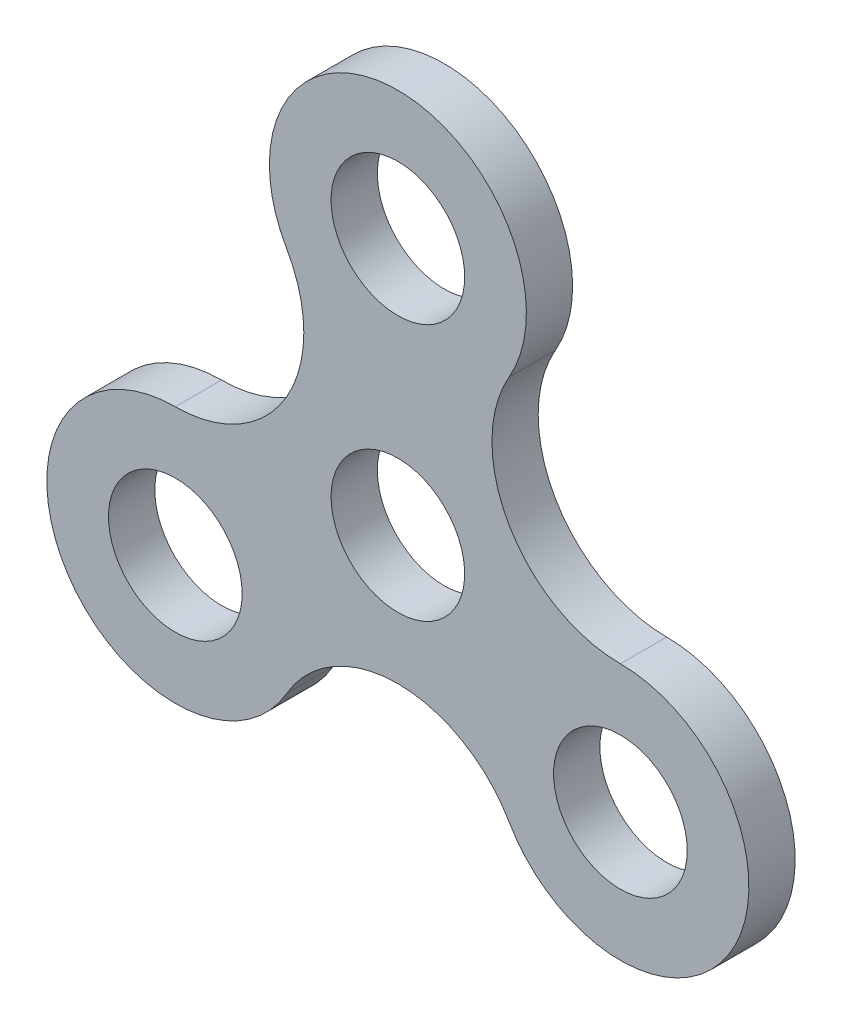
SolidWorks part; units mm, degrees
material "Alloy Steel"
ref_plane "Front Plane" through (0, 0, 0) normal (0, 0, 1) x (1, 0, 0)
ref_plane "Top Plane" through (0, 0, 0) normal (0, 1, 0) x (1, 0, 0)
ref_plane "Right Plane" through (0, 0, 0) normal (1, 0, 0) x (0, 0, -1)
sketch "Sketch1" plane through (0, 0, 0) normal (0, 0, 1) x (1, 0, 0)
  line L0 (0, 0) -> (0, 500) construction
  line L1 (0, 0) -> (-433.0127, -250) construction
  line L2 (0, 0) -> (433.0127, -250) construction
  circle A0 centre (0, 0) radius 750 construction
  circle A1 centre (0, 0) radius 250 construction
  arc A3 (-433.0127, 0) -> (-216.5064, -375) centre (-433.0127, -250) ccw
  arc A4 (216.5064, -375) -> (433.0127, 0) centre (433.0127, -250) ccw
  arc A5 (216.5064, 375) -> (-216.5064, 375) centre (0, 500) ccw
  arc A6 (-433.0127, 0) -> (-216.5064, 375) centre (-433.0127, 250) ccw
  arc A7 (216.5064, 375) -> (433.0127, 0) centre (433.0127, 250) ccw
  arc A8 (216.5064, -375) -> (-216.5064, -375) centre (0, -500) ccw
  dimension "D1" = 1500
  dimension "D2" = 500
  dimension "D3" = 120
  dimension "D4" = 120
extrude "Boss-Extrude1" add sketch "Sketch1" along normal mid plane 90
sketch "Sketch2" plane through (0, 0, 45) normal (0, 0, 1) x (1, 0, 0)
  circle A0 centre (-433.0127, -250) radius 130
  circle A1 centre (433.0127, -250) radius 130
  circle A2 centre (0, 500) radius 130
  dimension "D1" = 260
sketch "Sketch3" plane through (0, 0, -45) normal (0, 0, -1) x (-1, 0, 0)
  circle A0 centre (0, 0) radius 130
  dimension "D1" = 260
extrude "Cut-Extrude1" cut sketch "Sketch3" against normal through all
extrude "Cut-Extrude2" cut sketch "Sketch2" against normal through all
